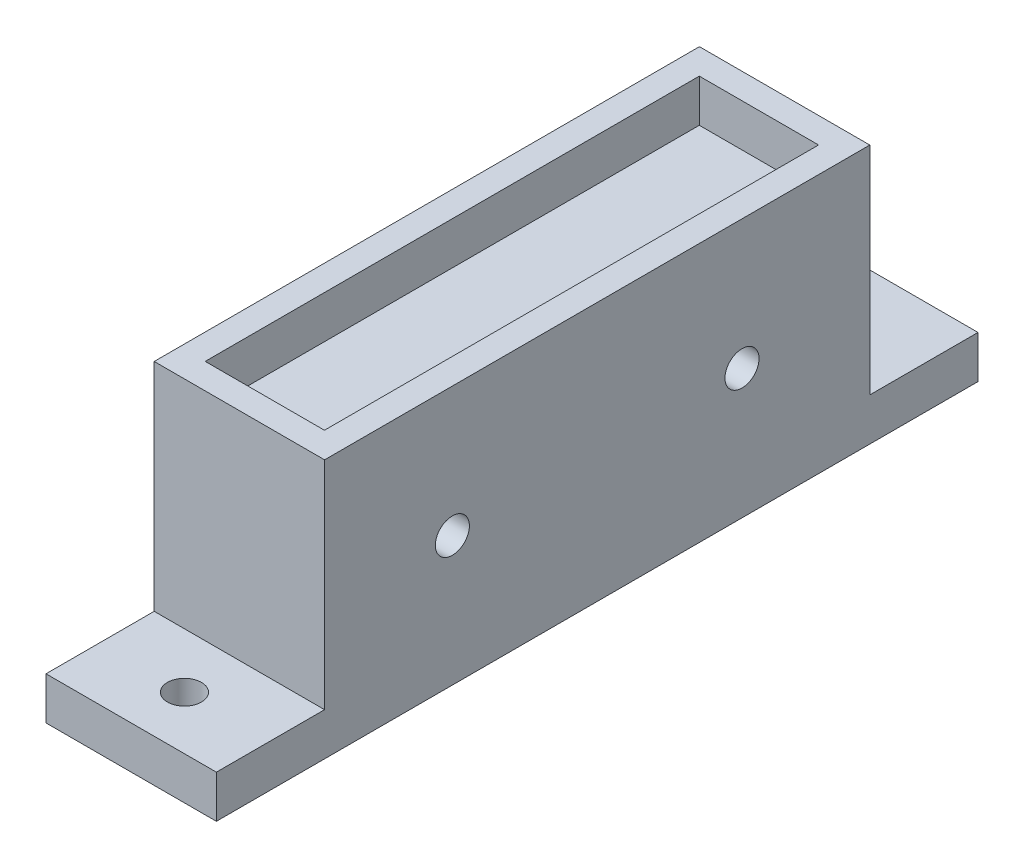
SolidWorks part; units mm, degrees
ref_plane "Front Plane" through (0, 0, 0) normal (0, 0, 1) x (1, 0, 0)
ref_plane "Top Plane" through (0, 0, 0) normal (0, 1, 0) x (1, 0, 0)
ref_plane "Right Plane" through (0, 0, 0) normal (1, 0, 0) x (0, 0, -1)
sketch "Sketch1" plane through (0, 0, 0) normal (1, 0, 0) x (0, 0, -1)
  line L0 (0, 0) -> (0, 5)
  line L1 (0, 5) -> (12.7, 5)
  line L2 (12.7, 5) -> (12.7, 30.4)
  line L3 (12.7, 30.4) -> (76.7, 30.4)
  line L4 (76.7, 30.4) -> (76.7, 5)
  line L5 (76.7, 5) -> (89.4, 5)
  line L6 (89.4, 5) -> (89.4, 0)
  line L7 (89.4, 0) -> (0, 0)
  dimension "D1" = 12.7
  dimension "D2" = 12.7
  dimension "D3" = 25.4
  dimension "D4" = 5
  dimension "D5" = 64
extrude "Boss-Extrude1" add sketch "Sketch1" along normal blind 20
sketch "Sketch2" plane through (0, 0, 0) normal (0, 1, 0) x (1, 0, 0)
  line L0 (-40.8574, 44.7) -> (56.8373, 44.7) construction
  line L5 (20, 76.7) -> (0, 76.7) construction
  line L6 (20, 12.7) -> (0, 12.7) construction
  line L7 (10, 91.4048) -> (10, -8.5958) construction
  line L8 (0, 76.7) -> (0, 12.7) construction
  line L9 (20, 76.7) -> (20, 12.7) construction
sketch "Sketch4" plane through (0, 30.4, 0) normal (0, 1, 0) x (1, 0, 0)
  line L0 (-40.8574, 44.7) -> (56.8373, 44.7) construction
  line L1 (2.9864, 73.7) -> (16.9864, 73.7)
  line L2 (2.9864, 73.7) -> (2.9864, 15.7)
  line L3 (2.9864, 15.7) -> (16.9864, 15.7)
  line L4 (16.9864, 73.7) -> (16.9864, 15.7)
  line L5 (2.9864, 73.7) -> (16.9864, 15.7) construction
  line L6 (2.9864, 15.7) -> (16.9864, 73.7) construction
  point P0 (9.9864, 44.7)
  dimension "D1" = 14
  dimension "D2" = 58
extrude "Cut-Extrude1" cut sketch "Sketch4" against normal blind 5
sketch "Sketch5" plane through (0, 5, 0) normal (0, 1, 0) x (1, 0, 0)
  line L0 (10, 91.4048) -> (10, -8.5958) construction
  line L1 (20, 89.4) -> (0, 89.4) construction
  line L2 (20, 0) -> (0, 0) construction
  circle A0 centre (10, 83.15) radius 2
  circle A1 centre (10, 6.25) radius 2
  dimension "D1" = 6.25
  dimension "D2" = 6.25
  dimension "D3" = 4
  dimension "D4" = 4
extrude "Cut-Extrude2" cut sketch "Sketch5" against normal blind 5
sketch "Sketch6" plane through (0, 0, 0) normal (1, 0, 0) x (0, 0, -1)
  line L0 (27.7, 38.9062) -> (27.7, -14.8826) construction
  line L1 (61.7, 38.9062) -> (61.7, -14.8826) construction
  line L2 (12.7, 30.4) -> (12.7, 5) construction
  line L4 (76.7, 5) -> (76.7, 30.4) construction
  line L5 (0, 15.2) -> (74.9325, 15.2) construction
  line L6 (76.7, 30.4) -> (12.7, 30.4) construction
  line L7 (91.4048, 0) -> (-8.5958, 0) construction
  circle A0 centre (27.7, 15.2) radius 2
  circle A1 centre (61.7, 15.2) radius 2
  dimension "D3" = 4
  dimension "D4" = 4
  dimension "D1" = 15
  dimension "D2" = 15
extrude "Cut-Extrude3" cut sketch "Sketch6" against normal blind 5 and the other way through all
